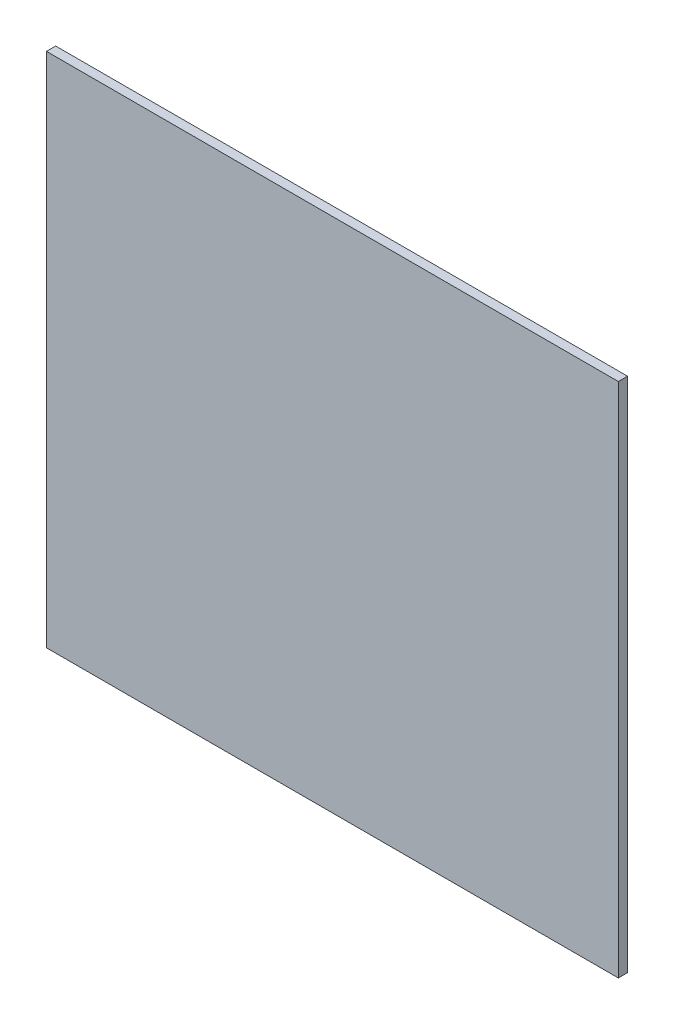
SolidWorks part; units mm, degrees
ref_plane "Ebene vorne" through (0, 0, 0) normal (0, 0, 1) x (1, 0, 0)
ref_plane "Ebene oben" through (0, 0, 0) normal (0, 1, 0) x (1, 0, 0)
ref_plane "Ebene rechts" through (0, 0, 0) normal (1, 0, 0) x (0, 0, -1)
sketch "Skizze1" plane through (0, 0, 0) normal (0, 0, 1) x (1, 0, 0)
  line L1 (-155, 140) -> (155, 140)
  line L2 (-155, 140) -> (-155, -140)
  line L3 (-155, -140) -> (155, -140)
  line L4 (155, 140) -> (155, -140)
  line L5 (-155, 140) -> (155, -140) construction
  line L6 (-155, -140) -> (155, 140) construction
  point P0 (0, 0)
  dimension "D1" = 280
  dimension "D2" = 310
extrude "Aufsatz-Linear austragen1" add sketch "Skizze1" along normal blind 5
